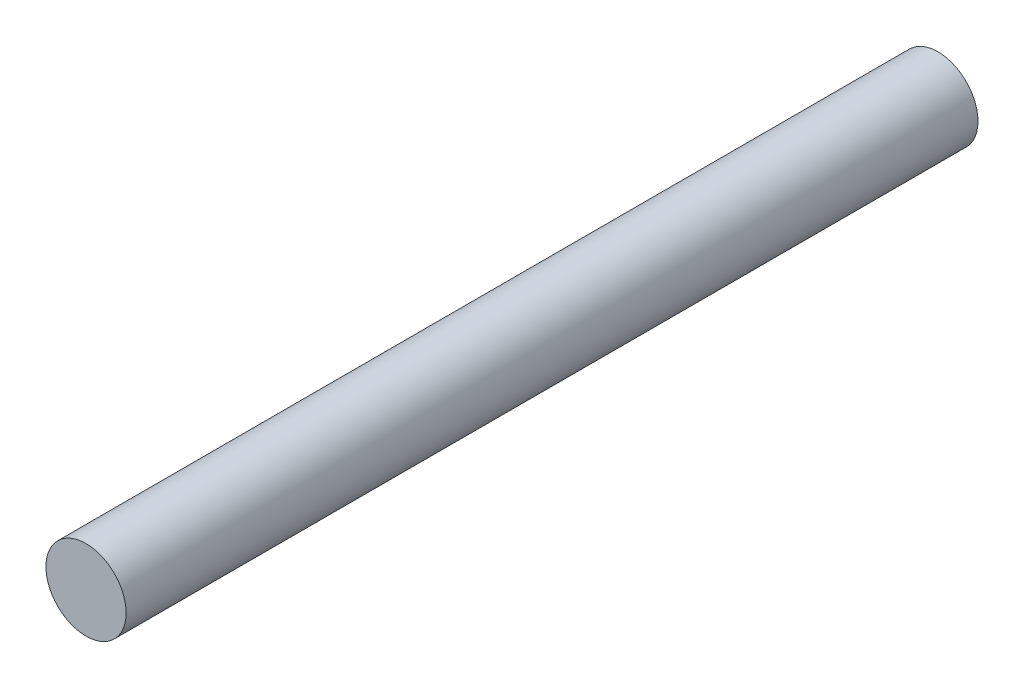
SolidWorks part; units mm, degrees
ref_plane "Спереди" through (0, 0, 0) normal (0, 0, 1) x (1, 0, 0)
ref_plane "Сверху" through (0, 0, 0) normal (0, 1, 0) x (1, 0, 0)
ref_plane "Справа" through (0, 0, 0) normal (1, 0, 0) x (0, 0, -1)
sketch "Эскиз1" plane through (0, 0, 0) normal (0, 0, 1) x (1, 0, 0)
  circle A0 centre (0, 0) radius 2
extrude "Бобышка-Вытянуть1" add sketch "Эскиз1" along normal blind 42.5
